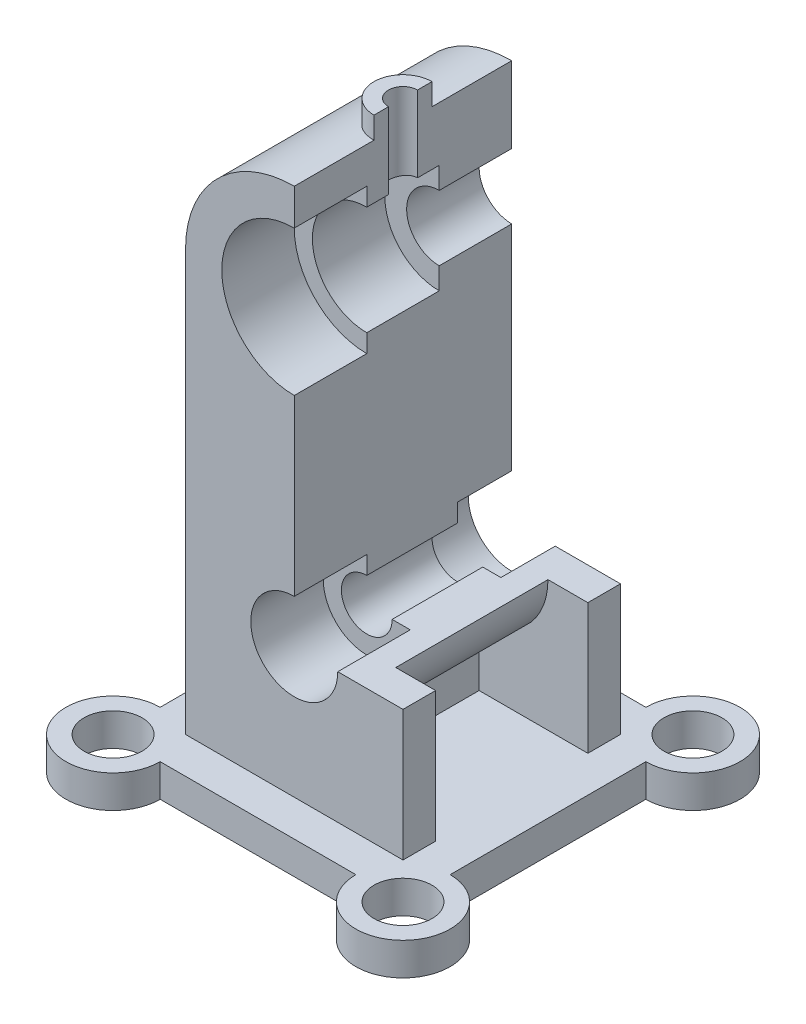
SolidWorks part; units mm, degrees
ref_plane "Ön Düzlem" through (0, 0, 0) normal (0, 0, 1) x (1, 0, 0)
ref_plane "Üst Düzlem" through (0, 0, 0) normal (0, 1, 0) x (1, 0, 0)
ref_plane "Sağ Düzlem" through (0, 0, 0) normal (1, 0, 0) x (0, 0, -1)
sketch "Sketch1" plane through (0, 0, 0) normal (0, 1, 0) x (1, 0, 0)
  line L0 (40, -27) -> (40, 27)
  line L6 (-27, -40) -> (27, -40)
  line L7 (-40, -27) -> (-40, 27)
  line L8 (-27, 40) -> (27, 40)
  arc A0 (-27, 40) -> (-40, 27) centre (-40, 40) ccw
  circle A1 centre (-40, 40) radius 8
  circle A2 centre (-40, -40) radius 8
  arc A3 (-40, -27) -> (-27, -40) centre (-40, -40) ccw
  circle A4 centre (40, -40) radius 8
  arc A5 (27, -40) -> (40, -27) centre (40, -40) ccw
  circle A6 centre (40, 40) radius 8
  arc A7 (40, 27) -> (27, 40) centre (40, 40) ccw
  point P0 (0, 0)
  dimension "D3" = 26
  dimension "D4" = 16
extrude "Boss-Extrude1" add sketch "Sketch1" along normal blind 9
sketch "Sketch3" plane through (0, 0, 0) normal (1, 0, 0) x (0, 0, -1)
  line L0 (53, 9) -> (27, 9) construction
  line L1 (30, 9) -> (-30, 9)
  line L2 (30, 9) -> (30, 125)
  line L3 (30, 125) -> (-30, 125)
  line L4 (-30, 9) -> (-30, 125)
  dimension "D1" = 10
  dimension "D2" = 60
  dimension "D3" = 116
extrude "Boss-Extrude2" add sketch "Sketch3" along normal mid plane 60
sketch "Sketch4" plane through (0, 0, 30) normal (0, 0, 1) x (1, 0, 0)
  line L0 (30, 125) -> (-30, 125) construction
  circle A0 centre (0, 125) radius 30
extrude "Boss-Extrude3" add sketch "Sketch4" against normal up to surface (60 mm away) up to face at (0, 67, -30)
ref_plane "Plane2" through (0, 161, 0) normal (0, 1, 0) x (1, 0, 0)
sketch "Sketch6" plane through (0, 161, 0) normal (0, 1, 0) x (1, 0, 0)
  circle A0 centre (0, 0) radius 8
  circle A1 centre (0, 0) radius 4
  dimension "D1" = 16
  dimension "D2" = 8
extrude "Boss-Extrude4" add sketch "Sketch6" against normal blind 20
sketch "Sketch7" plane through (0, 0, 30) normal (0, 0, 1) x (1, 0, 0)
  line L0 (8, 161) -> (-8, 161) construction
  line L1 (0, 161) -> (53.6248, 161)
  line L2 (0, 161) -> (0, 45)
  line L3 (0, 45) -> (53.6248, 45)
  line L4 (53.6248, 161) -> (53.6248, 45)
  line L5 (53, 9) -> (27, 9) construction
  dimension "D1" = 36
extrude "Cut-Extrude2" cut sketch "Sketch7" against normal through all
sketch "Sketch8" plane through (0, 0, 30) normal (0, 0, 1) x (1, 0, 0)
  circle A0 centre (0, 45) radius 12
  dimension "D1" = 24
extrude "Cut-Extrude3" cut sketch "Sketch8" against normal through all
ref_plane "Plane3" through (0, 0, -15) normal (0, 0, -1) x (-1, 0, 0)
sketch "Sketch9" plane through (0, 0, -15) normal (0, 0, -1) x (-1, 0, 0)
  line L0 (-12, 45) -> (-7, 45)
  line L1 (0, 52) -> (0, 57)
  arc A0 (-12, 45) -> (0, 57) centre (0, 45) ccw
  arc A1 (-7, 45) -> (0, 52) centre (0, 45) ccw
  dimension "D1" = 14
extrude "Boss-Extrude5" add sketch "Sketch9" against normal blind 25
sketch "Sketch10" plane through (0, 0, 30) normal (0, 0, 1) x (1, 0, 0)
  circle A0 centre (0, 125) radius 20
  dimension "D1" = 40
extrude "Cut-Extrude4" cut sketch "Sketch10" against normal blind 20
sketch "Sketch11" plane through (0, 0, 10) normal (0, 0, 1) x (1, 0, 0)
  line L0 (0, 105) -> (0, 145) construction
  circle A0 centre (0, 125) radius 15
  dimension "D1" = 30
extrude "Cut-Extrude5" cut sketch "Sketch11" against normal blind 20
sketch "Sketch12" plane through (0, 0, -10) normal (0, 0, 1) x (1, 0, 0)
  circle A0 centre (0, 125) radius 9
  dimension "D1" = 18
extrude "Cut-Extrude6" cut sketch "Sketch12" against normal through all
sketch "Sketch13" plane through (0, 161, 0) normal (0, 1, 0) x (1, 0, 0)
  circle A0 centre (0, 0) radius 4
extrude "Cut-Extrude7" cut sketch "Sketch13" against normal blind 31
ref_plane "Plane4" through (0, 0, 21) normal (0, 0, 1) x (1, 0, 0)
sketch "Sketch14" plane through (0, 0, 21) normal (0, 0, 1) x (1, 0, 0)
  line L0 (19, 45) -> (30, 45)
  line L1 (30, 45) -> (30, 9)
  line L2 (30, 9) -> (0, 9)
  line L3 (-27, 9) -> (27, 9) construction
  line L4 (0, 9) -> (0, 26)
  arc A0 (0, 26) -> (19, 45) centre (0, 45) ccw
  dimension "D1" = 38
extrude "Cut-Extrude8" cut sketch "Sketch14" against normal blind 42
